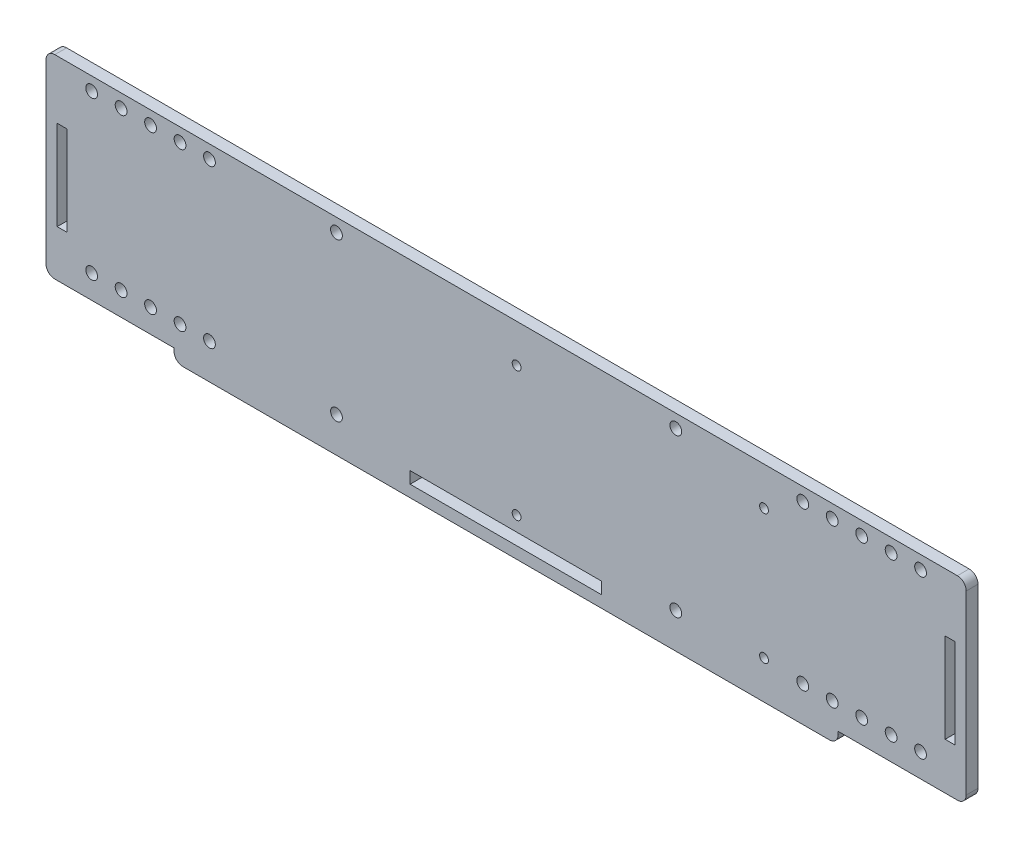
SolidWorks part; units mm, degrees
ref_plane "Front Plane" through (0, 0, 0) normal (0, 0, 1) x (1, 0, 0)
ref_plane "Top Plane" through (0, 0, 0) normal (0, 1, 0) x (1, 0, 0)
ref_plane "Right Plane" through (0, 0, 0) normal (1, 0, 0) x (0, 0, -1)
sketch "Sketch1" plane through (0, 0, 0) normal (0, 0, 1) x (1, 0, 0)
  line L0 (0, 71.7209) -> (0, -66.4222) construction
  line L1 (-156.215, 33) -> (156.215, 33)
  line L2 (-156.215, 33) -> (-156.215, -33)
  line L4 (156.215, 33) -> (156.215, -33)
  line L5 (-156.215, 33) -> (156.215, -33) construction
  line L6 (-156.215, -33) -> (156.215, 33) construction
  line L7 (-112.73, -33) -> (-112.73, -37)
  line L8 (-112.73, -37) -> (112.73, -37)
  line L9 (112.73, -33) -> (112.73, -37)
  line L10 (-156.215, -33) -> (-112.73, -33)
  line L11 (112.73, -33) -> (156.215, -33)
  line L12 (152.415, -17.18) -> (149.065, -17.18)
  line L13 (-152.415, 13.22) -> (-149.065, 13.22)
  line L14 (-152.415, 13.22) -> (-152.415, -17.18)
  line L15 (-152.415, -17.18) -> (-149.065, -17.18)
  line L16 (-149.065, 13.22) -> (-149.065, -17.18)
  line L17 (-32.585, -29) -> (32.415, -29)
  line L18 (-32.585, -29) -> (-32.585, -33)
  line L19 (-32.585, -33) -> (32.415, -33)
  line L20 (32.415, -29) -> (32.415, -33)
  line L21 (149.065, 13.22) -> (149.065, -17.18)
  line L22 (152.415, 13.22) -> (149.065, 13.22)
  line L23 (152.415, 13.22) -> (152.415, -17.18)
  circle A0 centre (-140.715, 28.5) radius 2
  circle A1 centre (-130.715, 28.5) radius 2
  circle A2 centre (-120.715, 28.5) radius 2
  circle A3 centre (-110.715, 28.5) radius 2
  circle A4 centre (-100.715, 28.5) radius 2
  circle A5 centre (-57.595, 28.5) radius 2
  circle A6 centre (57.595, 28.5) radius 2
  circle A7 centre (100.715, 28.5) radius 2
  circle A8 centre (110.715, 28.5) radius 2
  circle A9 centre (120.715, 28.5) radius 2
  circle A10 centre (130.715, 28.5) radius 2
  circle A11 centre (140.715, 28.5) radius 2
  circle A12 centre (-140.715, -25) radius 2
  circle A13 centre (-130.715, -25) radius 2
  circle A14 centre (-120.715, -25) radius 2
  circle A15 centre (-110.715, -25) radius 2
  circle A16 centre (-100.715, -25) radius 2
  circle A17 centre (-57.595, -25) radius 2
  circle A18 centre (140.715, -25) radius 2
  circle A19 centre (130.715, -25) radius 2
  circle A20 centre (120.715, -25) radius 2
  circle A21 centre (110.715, -25) radius 2
  circle A22 centre (100.715, -25) radius 2
  circle A23 centre (57.595, -25) radius 2
  circle A24 centre (3.565, -24) radius 1.5
  circle A25 centre (3.565, 20) radius 1.5
  circle A26 centre (87.565, 20) radius 1.5
  circle A27 centre (87.565, -24) radius 1.5
  point P0 (0, 0)
  point P37 (0, -37)
  dimension "D3" = 4
  dimension "D4" = 4.5
  dimension "D5" = 15.5
  dimension "D7" = 4.5
  dimension "D9" = 4
  dimension "D11" = 112.73
  dimension "D13" = 4
  dimension "D14" = 8
  dimension "D15" = 15.5
  dimension "D17" = 10
  dimension "D18" = 3.35
  dimension "D26" = 4
  dimension "D27" = 12
  dimension "D28" = 98.62
  dimension "D29" = 152.65
  dimension "D30" = 13
  dimension "D31" = 3
  dimension "D32" = 3
  dimension "D33" = 13
  dimension "D34" = 152.65
  dimension "D35" = 3
  dimension "D36" = 68.65
  dimension "D37" = 13
  dimension "D38" = 3
  dimension "D39" = 68.65
  dimension "D40" = 13
  dimension "D1" = 66
  dimension "D2" = 312.43
  dimension "D8" = 98.62
  dimension "D10" = 10
  dimension "D12" = 4
  dimension "D19" = 30.4
  dimension "D20" = 3.8
  dimension "D21" = 19.78
  dimension "D22" = 65
  dimension "D23" = 4
  dimension "D24" = 4
  dimension "D25" = 123.8
  dimension "D6" = 5
  dimension "D16" = 5
extrude "Boss-Extrude1" add sketch "Sketch1" along normal blind 4
fillet "Fillet1" radius 3 6 edges at (156.215, 33, 2) (156.215, -33, 2) (112.73, -37, 2) (-112.73, -37, 2) (-156.215, -33, 2) (-156.215, 33, 2)
